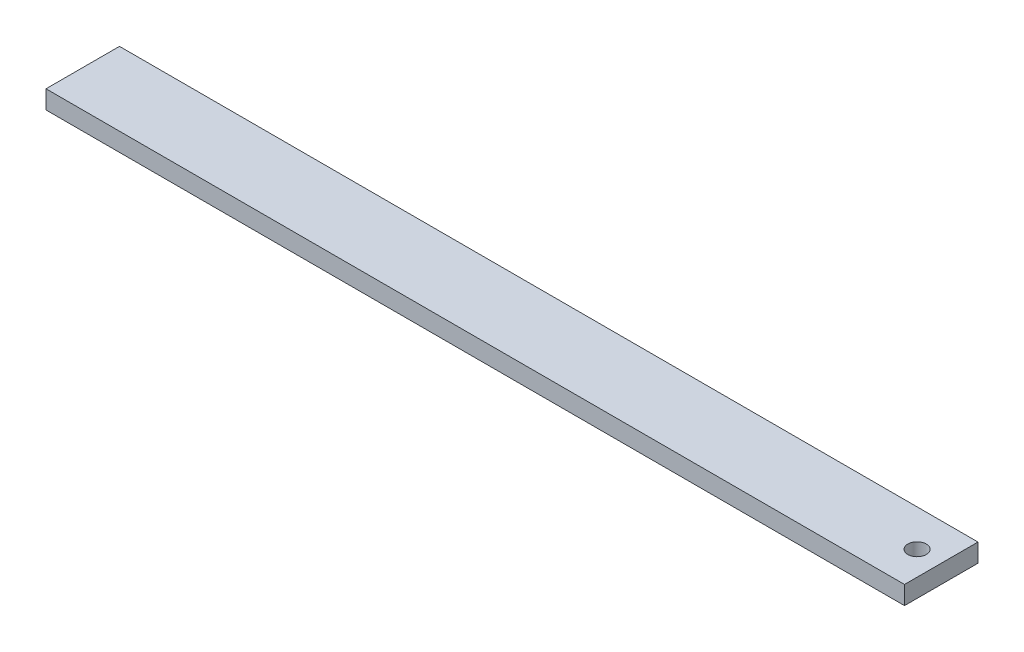
SolidWorks part; units mm, degrees
ref_plane "Front Plane" through (0, 0, 0) normal (0, 0, 1) x (1, 0, 0)
ref_plane "Top Plane" through (0, 0, 0) normal (0, 1, 0) x (1, 0, 0)
ref_plane "Right Plane" through (0, 0, 0) normal (1, 0, 0) x (0, 0, -1)
sketch "Sketch1" plane through (0, 0, 0) normal (0, 1, 0) x (1, 0, 0)
  line L1 (-140.2, -6) -> (140.2, -6)
  line L2 (-140.2, -6) -> (-140.2, 6)
  line L3 (-140.2, 6) -> (140.2, 6)
  line L4 (140.2, -6) -> (140.2, 6)
  line L5 (-140.2, -6) -> (140.2, 6) construction
  line L6 (-140.2, 6) -> (140.2, -6) construction
  point P0 (0, 0)
  dimension "D1" = 12
extrude "Boss-Extrude1" add sketch "Sketch1" along normal blind 3
sketch "Sketch3" plane through (0, 3, 0) normal (0, 1, 0) x (1, 0, 0)
  line L0 (-136.25, 0) -> (136.25, 0) construction
  circle A0 centre (-136.25, 0) radius 1.5
  circle A1 centre (136.25, 0) radius 1.5
  point P5 (0, 0)
  dimension "D1" = 1.5
  dimension "D2" = 272.5
extrude "Cut-Extrude1" cut sketch "Sketch3" against normal through all contours A1 | A0
sketch "Sketch4" plane through (0, 0, 0) normal (0, -1, 0) x (1, 0, 0)
  circle A0 centre (0, 0) radius 5
  dimension "D1" = 5
sketch "Sketch5" plane through (0, 3, 0) normal (0, 1, 0) x (1, 0, 0)
  line L0 (-140.2, 0) -> (140.2, 0) construction
  line L1 (-140.2, 6) -> (-140.2, -6) construction
  line L2 (140.2, -6) -> (140.2, 6) construction
sketch "Sketch6" plane through (0, 3, 0) normal (0, 1, 0) x (1, 0, 0)
  line L0 (-140.2, -6) -> (140.2, -6) construction
  line L1 (0, -6) -> (-140.2, -6)
  line L2 (0, -6) -> (0, 6)
  line L3 (0, 6) -> (-140.2, 6)
  line L4 (-140.2, -6) -> (-140.2, 6)
extrude "Cut-Extrude2" cut sketch "Sketch6" against normal through all
sketch "Sketch7" plane through (0, 0, 0) normal (-1, 0, 0) x (0, 0, 1)
  line L1 (-0.975, 0.525) -> (0.975, 0.525)
  line L2 (-0.975, 0.525) -> (-0.975, 2.475)
  line L3 (-0.975, 2.475) -> (0.975, 2.475)
  line L4 (0.975, 0.525) -> (0.975, 2.475)
  line L5 (-0.975, 0.525) -> (0.975, 2.475) construction
  line L6 (-0.975, 2.475) -> (0.975, 0.525) construction
  point P0 (0, 1.5)
  dimension "D1" = 1.95
extrude "Cut-Extrude3" cut sketch "Sketch7" against normal blind 4
fillet "Fillet1" radius 0.6 4 edges at (4, 0.525, 0) (4, 1.5, -0.975) (4, 2.475, 0) (4, 1.5, 0.975)
